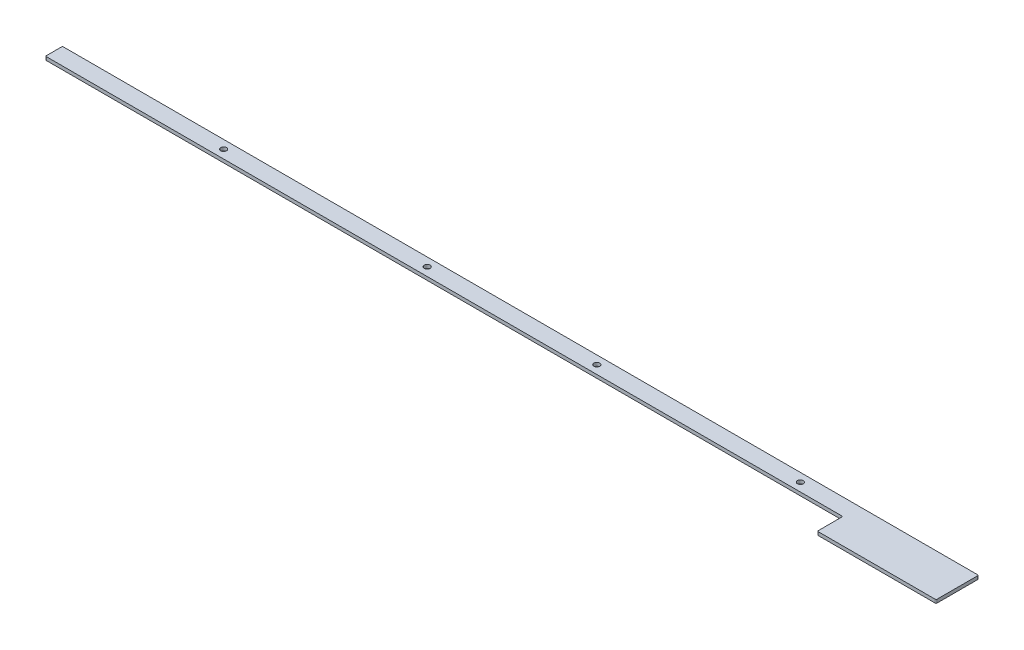
SolidWorks part; units mm, degrees
ref_plane "Front Plane" through (0, 0, 0) normal (0, 0, 1) x (1, 0, 0)
ref_plane "Top Plane" through (0, 0, 0) normal (0, 1, 0) x (1, 0, 0)
ref_plane "Right Plane" through (0, 0, 0) normal (1, 0, 0) x (0, 0, -1)
sketch "Sketch1" plane through (0, 0, 0) normal (0, 1, 0) x (1, 0, 0)
  line L1 (270, -5) -> (-270, -5)
  line L2 (270, -5) -> (270, 5)
  line L3 (270, 5) -> (-270, 5)
  line L4 (-270, -5) -> (-270, 5)
  line L5 (270, -5) -> (-270, 5) construction
  line L6 (270, 5) -> (-270, -5) construction
  point P0 (0, 0)
  dimension "D1" = 10
  dimension "D2" = 540
extrude "Boss-Extrude1" add sketch "Sketch1" along normal blind 2
sketch "Sketch2" plane through (0, 2, 0) normal (0, 1, 0) x (1, 0, 0)
  line L1 (270, -5) -> (200, -5)
  line L2 (270, -5) -> (270, -20)
  line L3 (270, -20) -> (200, -20)
  line L4 (200, -5) -> (200, -20)
  dimension "D1" = 70
  dimension "D2" = 15
extrude "Boss-Extrude2" add sketch "Sketch2" against normal blind 2
sketch "Sketch3" plane through (0, 2, 0) normal (0, 1, 0) x (1, 0, 0)
  point P0 (170, 0)
  point P2 (50, 0)
  point P4 (-50, 0)
  point P6 (-170, 0)
hole_wizard "M3 Clearance Hole1" positions "3DSketch1" profile "Sketch4" hole size "M3" standard "ANSI Metric"
sketch3d "3DSketch1"
  point P0 (-170, 2, 0)
  point P3 (-50, 2, 0)
  point P5 (50, 2, 0)
  point P8 (170, 2, 0)
sketch "Sketch4" plane through (-170, 2, 0) normal (1, 0, 0) x (0, 0, 1)
  line L0 (0, 0) -> (0, 11.0215)
  line L1 (0, 11.0215) -> (1.7, 10)
  line L2 (1.7, 10) -> (1.7, 0)
  line L5 (1.7, 0) -> (0, 0)
  line L10 (0, 11.0215) -> (-1.7, 10) construction
  line L11 (0, -6.35) -> (0, 107.95) construction
  dimension "Hole Dia." = 3.4
  dimension "Hole Depth" = 10
  dimension "Drill Angle" = 118
fillet "Fillet1" radius 0.5 6 edges at (-270, 1, 5) (200, 1, 5) (270, 1, 20) (270, 1, -5) (-270, 1, -5) (200, 1, 20)
